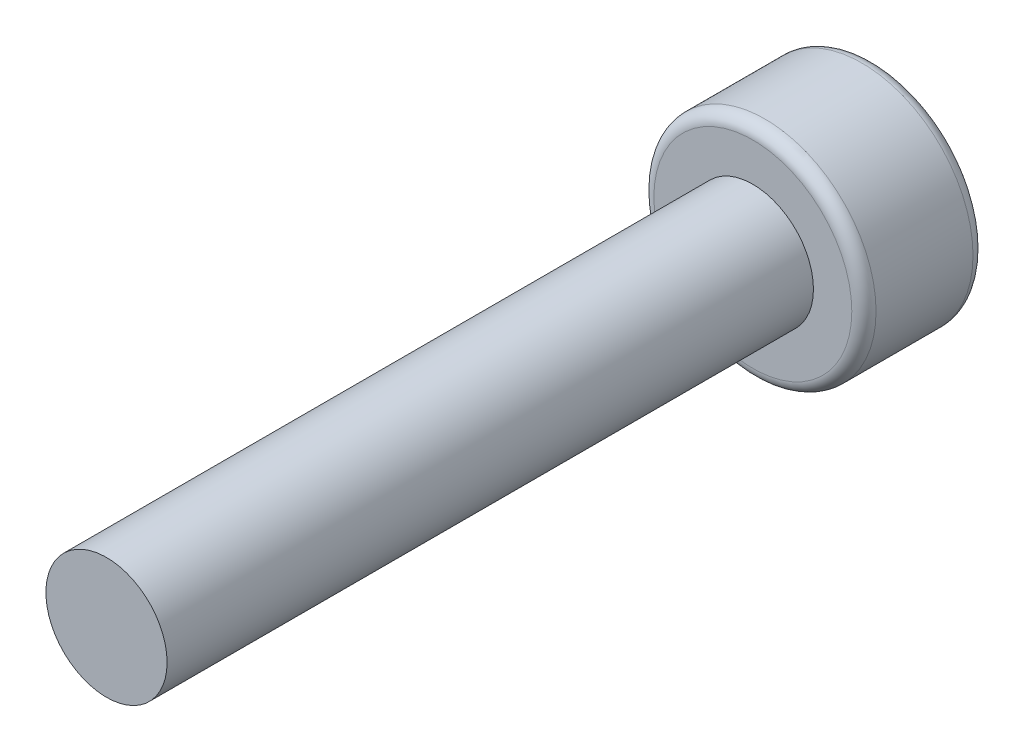
SolidWorks part; units mm, degrees
ref_plane "前视基准面" through (0, 0, 0) normal (0, 0, 1) x (1, 0, 0)
ref_plane "上视基准面" through (0, 0, 0) normal (0, 1, 0) x (1, 0, 0)
ref_plane "右视基准面" through (0, 0, 0) normal (1, 0, 0) x (0, 0, -1)
sketch "草图1" plane through (0, 0, 0) normal (0, 0, 1) x (1, 0, 0)
  circle A0 centre (0, 0) radius 2.75
  dimension "D1" = 2.75
extrude "凸台-拉伸1" add sketch "草图1" along normal blind 3
sketch "草图2" plane through (0, 0, 3) normal (0, 0, 1) x (1, 0, 0)
  circle A0 centre (0, 0) radius 1.5
  dimension "D1" = 1.5
extrude "凸台-拉伸2" add sketch "草图2" along normal blind 16
cosmetic thread "装饰螺纹线1" parameters "D2"=2
fillet "圆角1" radius 0.3 2 edges at (2.75, 0, 0) (2.75, 0, 3)
sketch "草图3" plane through (0, 0, 0) normal (0, 0, -1) x (-1, 0, 0)
  line L1 (-0.8209, 1.8624) -> (-2.0233, 0.2203)
  line L2 (-2.0233, 0.2203) -> (-1.2025, -1.6421)
  line L3 (-1.2025, -1.6421) -> (0.8209, -1.8624)
  line L4 (0.8209, -1.8624) -> (2.0233, -0.2203)
  line L5 (2.0233, -0.2203) -> (1.2025, 1.6421)
  line L6 (1.2025, 1.6421) -> (-0.8209, 1.8624)
  circle A0 centre (0, 0) radius 1.7626 construction
extrude "切除-拉伸1" cut sketch "草图3" against normal blind 2
